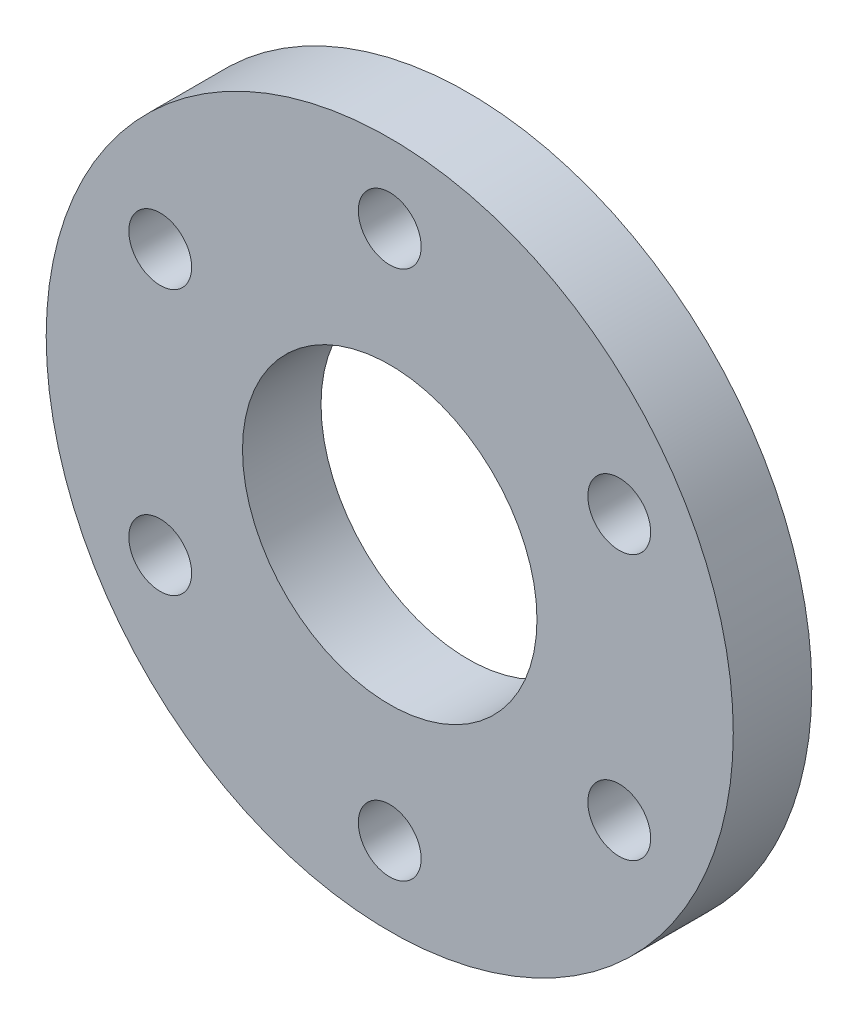
SolidWorks part; units mm, degrees
material "Thornel Mat VMA"
ref_plane "前视基准面" through (0, 0, 0) normal (0, 0, 1) x (1, 0, 0)
ref_plane "上视基准面" through (0, 0, 0) normal (0, 1, 0) x (1, 0, 0)
ref_plane "右视基准面" through (0, 0, 0) normal (1, 0, 0) x (0, 0, -1)
sketch "草图1" plane through (0, 0, 0) normal (0, 0, 1) x (1, 0, 0)
  circle A0 centre (0, 0) radius 7.5
  circle A1 centre (0, 0) radius 13.5 construction
  circle A2 centre (0, 0) radius 17.5
  circle A3 centre (0, 13.5) radius 1.6
  circle A4 centre (11.6913, 6.75) radius 1.6
  circle A5 centre (11.6913, -6.75) radius 1.6
  circle A6 centre (0, -13.5) radius 1.6
  circle A7 centre (-11.6913, -6.75) radius 1.6
  circle A8 centre (-11.6913, 6.75) radius 1.6
  point P20 (0, 0)
  dimension "D1" = 3.2
  dimension "D2" = 35
  dimension "D3" = 27
  dimension "D4" = 15
  dimension "D5" = 6
extrude "凸台-拉伸1" add sketch "草图1" along normal blind 4
